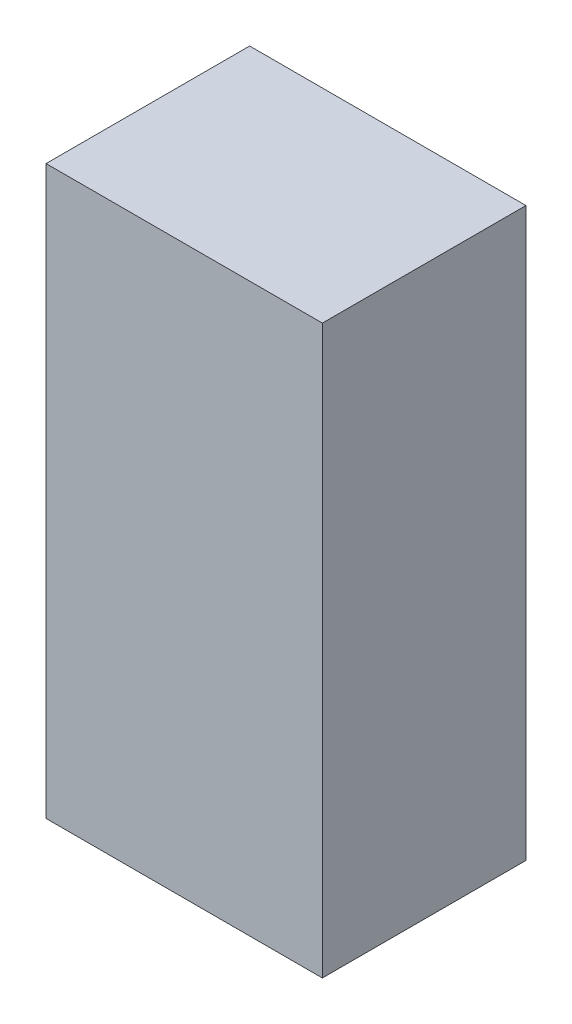
SolidWorks part; units mm, degrees
ref_plane "前视基准面" through (0, 0, 0) normal (0, 0, 1) x (1, 0, 0)
ref_plane "上视基准面" through (0, 0, 0) normal (0, 1, 0) x (1, 0, 0)
ref_plane "右视基准面" through (0, 0, 0) normal (1, 0, 0) x (0, 0, -1)
other "Configuration Table"
sketch "草图1" plane through (0, 0, 0) normal (0, 0, 1) x (1, 0, 0)
  line L1 (-19, -39) -> (19, -39)
  line L2 (-19, -39) -> (-19, 39)
  line L3 (-19, 39) -> (19, 39)
  line L4 (19, -39) -> (19, 39)
extrude "凸台-拉伸1" add sketch "草图1" against normal blind 28
